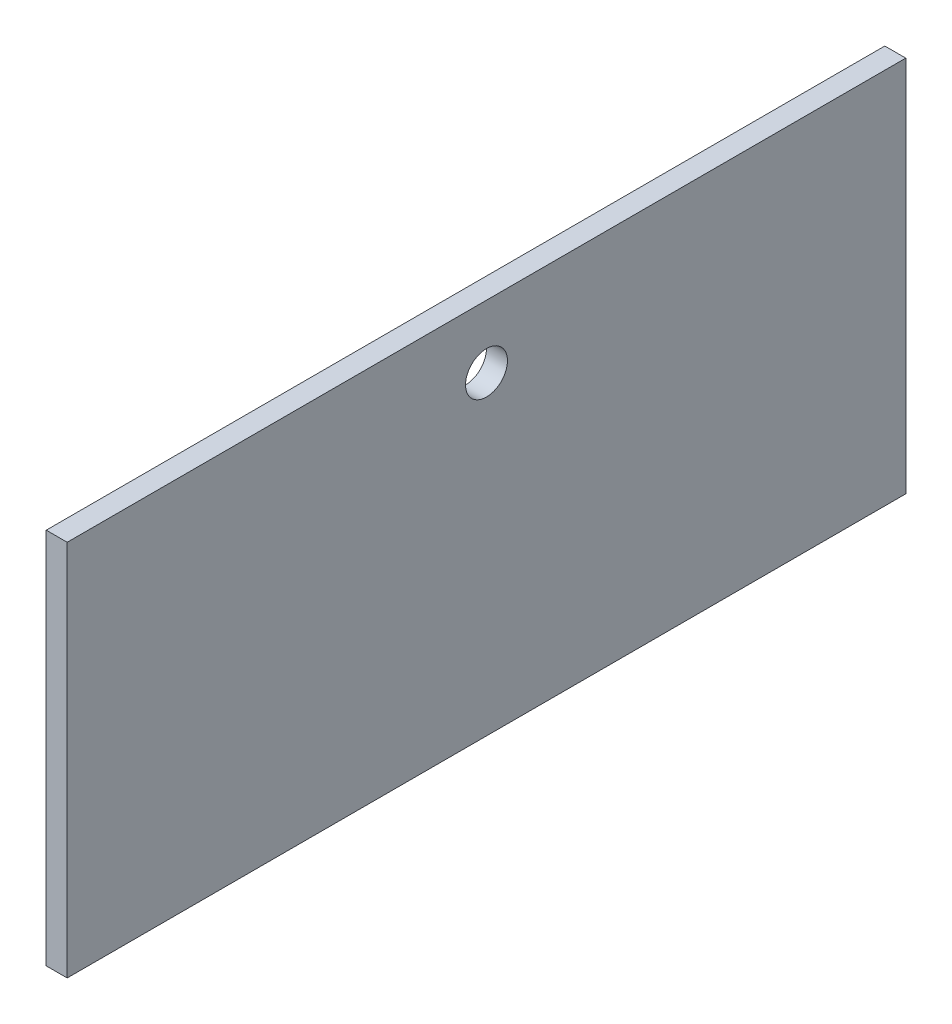
SolidWorks part; units mm, degrees
ref_plane "Front Plane" through (0, 0, 0) normal (0, 0, 1) x (1, 0, 0)
ref_plane "Top Plane" through (0, 0, 0) normal (0, 1, 0) x (1, 0, 0)
ref_plane "Right Plane" through (0, 0, 0) normal (1, 0, 0) x (0, 0, -1)
sketch "Sketch1" plane through (0, 0, 0) normal (0, 1, 0) x (1, 0, 0)
  line L1 (-75, 100) -> (75, 100)
  line L2 (-75, 100) -> (-75, -100)
  line L3 (-75, -100) -> (75, -100)
  line L4 (75, 100) -> (75, -100)
  line L5 (-75, 100) -> (75, -100) construction
  line L6 (-75, -100) -> (75, 100) construction
  point P0 (0, 0)
  dimension "D1" = 150
  dimension "D2" = 200
extrude "Boss-Extrude1" add sketch "Sketch1" along normal blind 100
shell "Shell2" thickness 5
sketch "Sketch5" plane through (0, 0, 0) normal (0, -1, 0) x (1, 0, 0)
  line L0 (-75, 100) -> (75, 100) construction
  circle A0 centre (-65, 91) radius 1.9
  circle A1 centre (-35, 91) radius 1.9
  circle A2 centre (-65, 67) radius 1.9
  circle A3 centre (-35, 67) radius 1.9
  dimension "D1" = 3.8
  dimension "D2" = 5
  dimension "D3" = 35
  dimension "D4" = 9
  dimension "D5" = 30
  dimension "D6" = 24
extrude "Cut-Extrude2" cut sketch "Sketch5" against normal blind 10
mirror "Mirror2" about plane through (0, 0, 0) normal (0, 0, 1) of "Cut-Extrude2"
sketch "Sketch6" plane through (0, 5, 0) normal (0, 1, 0) x (1, 0, 0)
  line L0 (-75, -100) -> (75, -100) construction
  line L1 (-70, 100) -> (-7.9429, 100) construction
  line L2 (-70, 100) -> (-70, -100) construction
  line L3 (-70, -100) -> (-7.9429, -100) construction
  line L4 (-7.9429, 100) -> (-7.9429, -100) construction
  line L10 (-70, -100) -> (-20, -100)
  line L11 (-70, -100) -> (-70, 100)
  line L12 (-70, 100) -> (-20, 100)
  line L13 (-20, -100) -> (-20, 100)
  dimension "D1" = 200
  dimension "D2" = 50
sketch "Sketch8" plane through (0, 0, 100) normal (0, 0, 1) x (1, 0, 0)
  line L3 (75, 17) -> (-15, 17)
  line L4 (-15, 0) -> (-15, 17)
  line L5 (75, 22) -> (-20, 22)
  line L6 (-20, 0) -> (-20, 22)
  line L8 (80, -5) -> (80, 22) construction
  line L9 (75, 0) -> (75, 17) construction
  line L10 (75, 0) -> (-15, 0) construction
  line L11 (80, -5) -> (-20, -5) construction
  line L12 (-15, 0) -> (-20, 0)
  line L13 (75, 17) -> (75, 22)
  line L14 (75, 100) -> (75, 0) construction
  line L15 (80, 22) -> (-20, 22) construction
  line L16 (-20, -5) -> (-20, 22) construction
  line L17 (-75, 0) -> (75, 0) construction
  line M3 (-75, 0) -> (75, 0)
  line M4 (75, 0) -> (75, 100)
  line M12 (70, 95) -> (70, 5)
  line M13 (70, 5) -> (-70, 5)
  dimension "D1" = 90
  dimension "D2" = 17
  dimension "D3" = 5
extrude "Boss-Extrude4" add sketch "Sketch8" against normal through all contours L6 L4 L3 L5 M13 M12 | L6 L4 M3 M13 | L5 L3 M4 M12
sketch "Sketch9" plane through (0, 0, 100) normal (0, 0, 1) x (1, 0, 0)
  line L1 (-15, 17) -> (86.1339, 17)
  line L2 (-15, 17) -> (-15, -14.9961)
  line L3 (-15, -14.9961) -> (86.1339, -14.9961)
  line L4 (86.1339, 17) -> (86.1339, -14.9961)
extrude "Cut-Extrude4" cut sketch "Sketch9" against normal through all
sketch "Sketch10" plane through (0, 17, 0) normal (0, -1, 0) x (1, 0, 0)
  line L0 (75, 100) -> (75, -100) construction
  circle A0 centre (60, 0) radius 4
  dimension "D1" = 8
  dimension "D2" = 15
extrude "Cut-Extrude5" cut sketch "Sketch10" against normal blind 10
sketch "Sketch11" plane through (0, 100, 0) normal (0, 1, 0) x (1, 0, 0)
  line L0 (-75, -100) -> (75, -100) construction
  line L1 (70, -95) -> (-70, -95)
  line L2 (70, -95) -> (70, -90)
  line L3 (70, -90) -> (-70, -90)
  line L4 (-70, -95) -> (-70, -90)
  line L5 (75, -100) -> (75, 100) construction
  line L6 (-75, 100) -> (-75, -100) construction
  point P6 (70, -92.5)
  dimension "D1" = 5
  dimension "D2" = 5
  dimension "D3" = 5
  dimension "D4" = 5
extrude "Cut-Extrude7" cut sketch "Sketch11" against normal up to surface (95 mm away) contours L4 L1 L2 L3 up to face at (-35, 5, -89.1)
mirror "Mirror3" about plane through (0, 0, 0) normal (0, 0, 1) of "Cut-Extrude7"
sketch "Sketch15" plane through (0, 100, 0) normal (0, 1, 0) x (1, 0, 0)
  circle A0 centre (50, 28) radius 1.2
  circle A1 centre (50, -28) radius 1.2
  circle A2 centre (-20, 20) radius 1.2
  circle A3 centre (-20, -20) radius 1.2
  dimension "D1" = 2.4
  dimension "D2" = 56
  dimension "D3" = 28
  dimension "D4" = 40
  dimension "D5" = 20
  dimension "D6" = 70
  dimension "D7" = 50
extrude "Cut-Extrude11" cut sketch "Sketch15" against normal blind 10
sketch "Sketch36" plane through (70, 0, 0) normal (-1, 0, 0) x (0, 0, 1)
  line L1 (-43.2021, 65) -> (16.7979, 65)
  line L2 (-43.2021, 65) -> (-43.2021, 60)
  line L3 (-43.2021, 60) -> (16.7979, 60)
  line L4 (16.7979, 65) -> (16.7979, 60)
  line L5 (-100, 0) -> (100, 0) construction
  point P6 (16.7979, 62.5)
  dimension "D1" = 65
  dimension "D2" = 5
  dimension "D3" = 16.7979
  dimension "D4" = 60
extrude "Boss-Extrude7" add sketch "Sketch36" along normal blind 10
mirror "Mirror5" about plane through (0, 0, 0) normal (1, 0, 0) of "Boss-Extrude7"
sketch "Sketch37" plane through (75, 0, 0) normal (1, 0, 0) x (0, 0, -1)
  circle A0 centre (0, 75) radius 3.5
  point P2 (0, 0)
  dimension "D1" = 7
  dimension "D2" = 75
extrude "Cut-Extrude15" cut sketch "Sketch37" against normal blind 60
sketch "Sketch38" plane through (-75, 0, 0) normal (-1, 0, 0) x (0, 0, 1)
  circle A0 centre (0, 80) radius 5
  point P2 (0, 0)
  dimension "D1" = 10
  dimension "D2" = 80
extrude "Cut-Extrude16" cut sketch "Sketch38" against normal blind 70
sketch "Sketch41" plane through (0, 0, 100) normal (0, 0, 1) x (1, 0, 0)
  line L0 (-70, 5) -> (-20, 5) construction
  line L1 (-70, 95) -> (91.4001, 95)
  line L2 (-70, 95) -> (-70, 5)
  line L3 (-70, 5) -> (91.4001, 5)
  line L4 (91.4001, 95) -> (91.4001, 5)
  line L6 (91.4001, 95) -> (-133.1779, 95)
  line L7 (91.4001, 95) -> (91.4001, 145.7142)
  line L8 (91.4001, 145.7142) -> (-133.1779, 145.7142)
  line L9 (-133.1779, 95) -> (-133.1779, 145.7142)
  line L10 (91.4001, 5) -> (-160.9045, 5)
  line L11 (91.4001, 5) -> (91.4001, -24.977)
  line L12 (91.4001, -24.977) -> (-160.9045, -24.977)
  line L13 (-160.9045, 5) -> (-160.9045, -24.977)
extrude "Cut-Extrude19" cut sketch "Sketch41" against normal through all contours L7 L6 L9 L8 | L2 L1 L4 L3 | L11 L10 L13 L12
